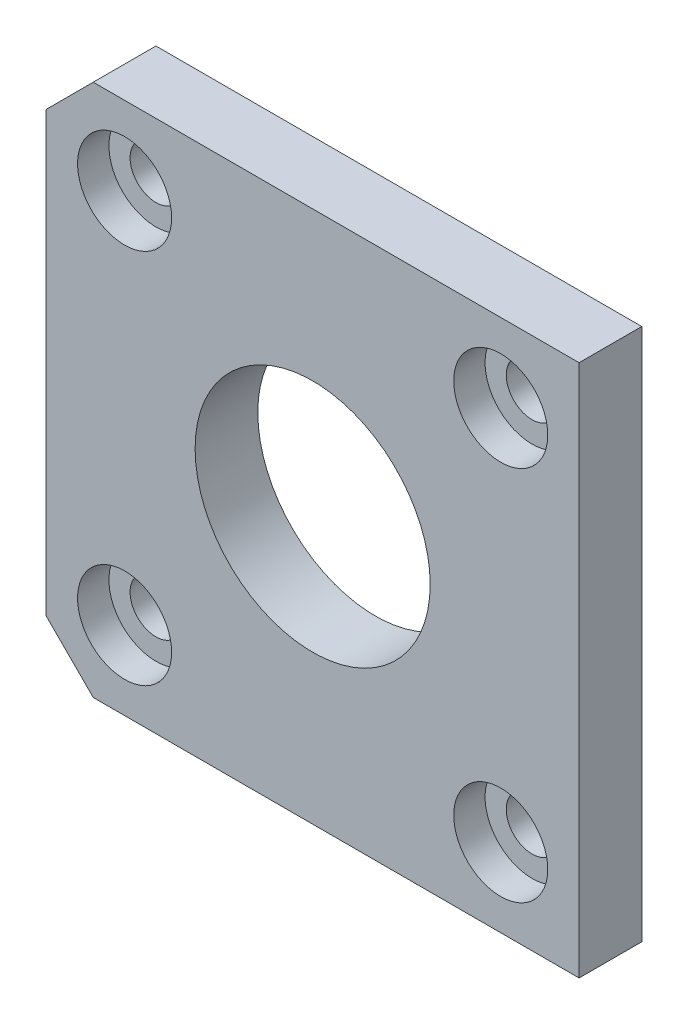
SolidWorks part; units mm, degrees
ref_plane "前视基准面" through (0, 0, 0) normal (0, 0, 1) x (1, 0, 0)
ref_plane "上视基准面" through (0, 0, 0) normal (0, 1, 0) x (1, 0, 0)
ref_plane "右视基准面" through (0, 0, 0) normal (1, 0, 0) x (0, 0, -1)
sketch "草图1" plane through (0, 0, 0) normal (0, 0, 1) x (1, 0, 0)
  line L0 (0, 31) -> (3, 34)
  line L1 (3, 0) -> (34, 0)
  line L2 (0, 3) -> (0, 31)
  line L3 (3, 34) -> (34, 34)
  line L4 (34, 0) -> (34, 34)
  line L5 (0, 3) -> (3, 0)
  circle A0 centre (17, 17) radius 7.5
  circle A1 centre (5, 29) radius 1.65
  circle A2 centre (29, 29) radius 1.65
  circle A3 centre (5, 5) radius 1.65
  circle A4 centre (29, 5) radius 1.65
  point P0 (0, 0)
  point P2 (0, 34)
  point P16 (0, 0)
  point P17 (0, 0)
  point P18 (0, 0)
  point P19 (0, 0)
  point P23 (4.5, 3.7592)
  point P24 (0, 17)
  dimension "D3" = 15
  dimension "D8" = 3.3
  dimension "D1" = 34
  dimension "D2" = 34
  dimension "D4" = 12
  dimension "D5" = 12
  dimension "D6" = 12
  dimension "D7" = 12
  dimension "D9" = 17
extrude "凸台-拉伸1" add sketch "草图1" along normal blind 4
sketch "草图2" plane through (0, 0, 4) normal (0, 0, 1) x (1, 0, 0)
  circle A0 centre (5, 29) radius 3
  circle A1 centre (29, 29) radius 3
  circle A2 centre (5, 5) radius 3
  circle A3 centre (29, 5) radius 3
  dimension "D1" = 6
extrude "切除-拉伸1" cut sketch "草图2" against normal blind 2
